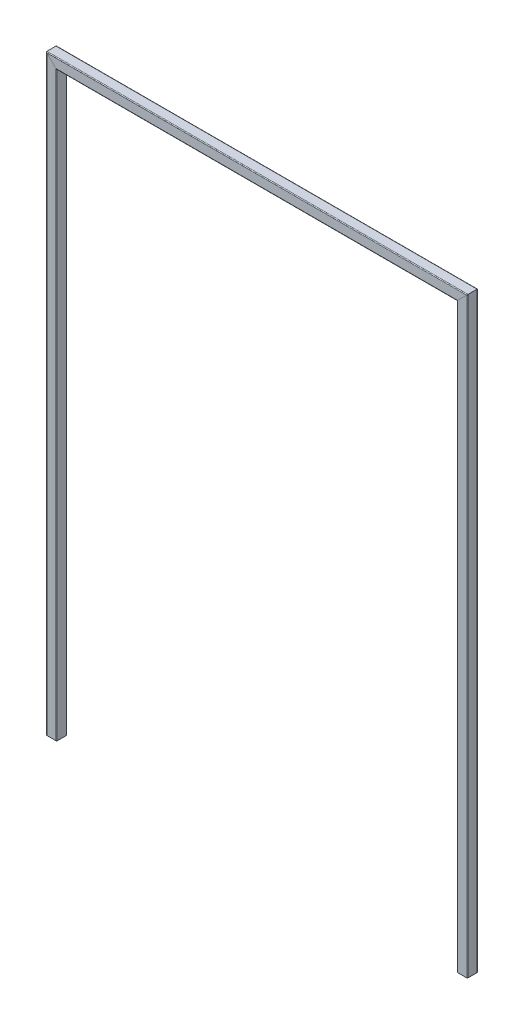
SolidWorks part; units mm, degrees
material "ASTM A36 Steel"
ref_plane "Front Plane" through (0, 0, 0) normal (0, 0, 1) x (1, 0, 0)
ref_plane "Top Plane" through (0, 0, 0) normal (0, 1, 0) x (1, 0, 0)
ref_plane "Right Plane" through (0, 0, 0) normal (1, 0, 0) x (0, 0, -1)
sketch "Sketch1" plane through (0, 0, 0) normal (0, 0, 1) x (1, 0, 0)
  line L0 (0, 0) -> (0, 10000)
  line L1 (0, 10000) -> (7000, 10000)
  line L2 (7000, 10000) -> (7000, 0)
  dimension "D1" = 10000
  dimension "D2" = 7000
other "Tube square TS7X7X0.25(1)"
ref_plane "Plane1" through (0, 0, 0) normal (0, 1, 0) x (-1, 0, 0)
sketch "Sketch11" plane through (0, 0, 0) normal (0, 1, 0) x (-1, 0, 0)
  line L0 (-76.2, -82.55) -> (76.2, -82.55)
  line L1 (-82.55, -76.2) -> (-82.55, 76.2)
  line L2 (76.2, 82.55) -> (-76.2, 82.55)
  line L3 (82.55, 76.2) -> (82.55, -76.2)
  line L4 (-76.2, -88.9) -> (76.2, -88.9)
  line L5 (-88.9, -76.2) -> (-88.9, 76.2)
  line L6 (76.2, 88.9) -> (-76.2, 88.9)
  line L7 (88.9, 76.2) -> (88.9, -76.2)
  line L8 (-88.9, 0) -> (-82.55, 0) construction
  line L9 (-82.55, 0) -> (82.55, 0) construction
  line L10 (82.55, 0) -> (88.9, 0) construction
  line L11 (0, 88.9) -> (0, 82.55) construction
  line L12 (0, 82.55) -> (0, -82.55) construction
  line L13 (0, -82.55) -> (0, -88.9) construction
  arc A0 (88.9, 76.2) -> (76.2, 88.9) centre (76.2, 76.2) ccw
  arc A1 (76.2, -88.9) -> (88.9, -76.2) centre (76.2, -76.2) ccw
  arc A2 (-88.9, -76.2) -> (-76.2, -88.9) centre (-76.2, -76.2) ccw
  arc A3 (-76.2, 88.9) -> (-88.9, 76.2) centre (-76.2, 76.2) ccw
  arc A4 (-76.2, 82.55) -> (-82.55, 76.2) centre (-76.2, 76.2) ccw
  arc A5 (82.55, 76.2) -> (76.2, 82.55) centre (76.2, 76.2) ccw
  arc A6 (76.2, -82.55) -> (82.55, -76.2) centre (76.2, -76.2) ccw
  arc A7 (-82.55, -76.2) -> (-76.2, -82.55) centre (-76.2, -76.2) ccw
  point P6 (-88.9, -88.9)
  point P33 (-88.9, 88.9)
  point P35 (88.9, 88.9)
  point P36 (88.9, -88.9)
  point P37 (0, 0)
  point P38 (0, 0)
  dimension "D1" = 12.7
  dimension "Thickness" = 6.35
  dimension "V_leg" = 177.8
  dimension "H_leg" = 177.8
